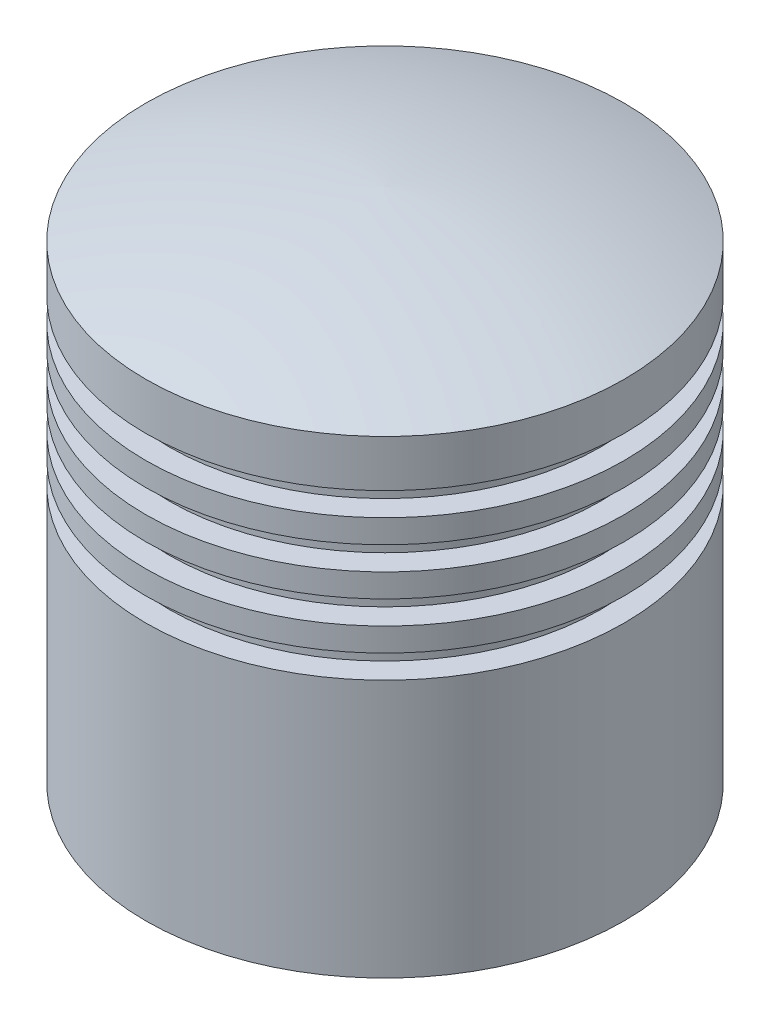
SolidWorks part; units mm, degrees
ref_plane "Front Plane" through (0, 0, 0) normal (0, 0, 1) x (1, 0, 0)
ref_plane "Top Plane" through (0, 0, 0) normal (0, 1, 0) x (1, 0, 0)
ref_plane "Right Plane" through (0, 0, 0) normal (1, 0, 0) x (0, 0, -1)
sketch "Sketch1" plane through (0, 0, 0) normal (0, 0, 1) x (1, 0, 0)
  line L0 (43, 0) -> (43, 30)
  line L1 (43, 0) -> (51, 0)
  line L2 (36, 30) -> (36, 97.4105)
  line L4 (51, 0) -> (51, 55)
  line L5 (43, 30) -> (36, 30)
  line L6 (51, 90) -> (51, 100)
  line L7 (0, 0) -> (0, 110) construction
  line L8 (0, 102.9941) -> (0, 110)
  line L9 (51, 85) -> (46, 85)
  line L10 (46, 85) -> (46, 90)
  line L11 (46, 90) -> (51, 90)
  line L12 (51, 75) -> (46, 75)
  line L13 (46, 80) -> (51, 80)
  line L14 (46, 75) -> (46, 80)
  line L15 (51, 65) -> (46, 65)
  line L16 (46, 70) -> (51, 70)
  line L17 (46, 65) -> (46, 70)
  line L18 (51, 55) -> (46, 55)
  line L19 (46, 60) -> (51, 60)
  line L20 (46, 55) -> (46, 60)
  line L21 (51, 80) -> (51, 85)
  line L22 (51, 70) -> (51, 75)
  line L23 (51, 60) -> (51, 65)
  arc A4 (51, 100) -> (0, 110) centre (-6.8261, -59.8629) ccw
  arc A7 (36, 97.4105) -> (0, 102.9941) centre (-6.8261, -59.8629) ccw
  point P15 (0, 0)
  point P28 (46, 55.0703)
  point P29 (0, 0)
  point P30 (0, 0)
  point P31 (46, 63.0927)
  dimension "D7" = 110
  dimension "D8" = 340
  dimension "D9" = 326
  dimension "D2" = 7
  dimension "D3" = 30
  dimension "D4" = 8
  dimension "D5" = 100
  dimension "D6" = 43
  dimension "D10" = 5
  dimension "D11" = 90
revolve "Revolve1" add sketch "Sketch1" angle 360 about L7
